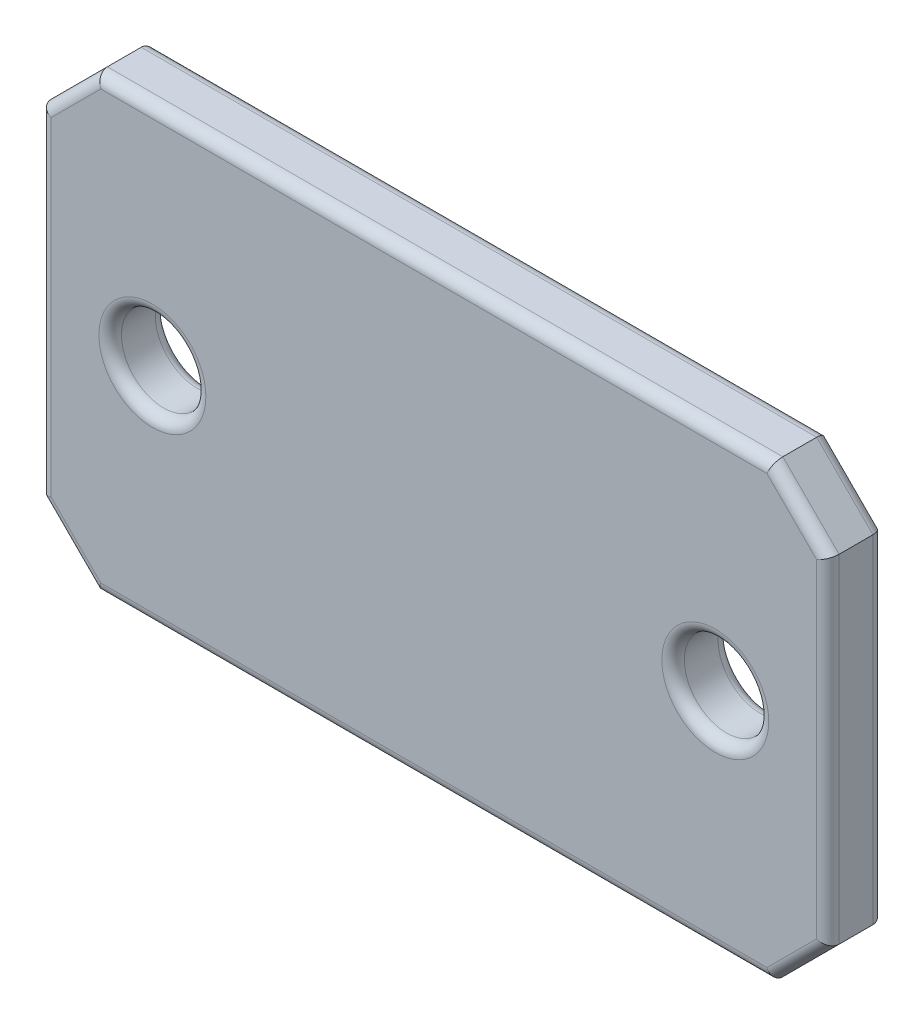
SolidWorks part; units mm, degrees
ref_plane "Front" through (0, 0, 0) normal (0, 0, 1) x (1, 0, 0)
ref_plane "Top" through (0, 0, 0) normal (0, 1, 0) x (1, 0, 0)
ref_plane "Right" through (0, 0, 0) normal (1, 0, 0) x (0, 0, -1)
sketch "Sketch1" plane through (0, 0, 0) normal (0, 0, 1) x (1, 0, 0)
  line L8 (19.05, 12.7) -> (-19.05, 12.7)
  line L9 (-19.05, 12.7) -> (-22.225, 9.525)
  line L10 (-22.225, 9.525) -> (-22.225, -9.525)
  line L11 (-22.225, -9.525) -> (-19.05, -12.7)
  line L12 (-19.05, -12.7) -> (19.05, -12.7)
  line L13 (19.05, -12.7) -> (22.225, -9.525)
  line L14 (22.225, -9.525) -> (22.225, 9.525)
  line L15 (22.225, 9.525) -> (19.05, 12.7)
  line L16 (19.05, 12.7) -> (-19.05, 12.7)
  line L17 (-19.05, 12.7) -> (-22.225, 9.525)
  line L18 (-22.225, 9.525) -> (-22.225, -9.525)
  line L19 (-22.225, -9.525) -> (-19.05, -12.7)
  line L20 (-19.05, -12.7) -> (19.05, -12.7)
  line L21 (19.05, -12.7) -> (22.225, -9.525)
  line L22 (22.225, -9.525) -> (22.225, 9.525)
  line L23 (22.225, 9.525) -> (19.05, 12.7)
  dimension "D1" = 0
extrude "Boss-Extrude1" add sketch "Sketch1" along normal blind 3.175
hole_wizard "3/16 (0.1875) Diameter Hole1" positions "Sketch2" profile "Sketch3" hole size "3/16" standard "ANSI Inch" end condition through all
sketch "Sketch2" plane through (0, 0, 3.175) normal (0, 0, 1) x (1, 0, 0)
  circle A0 centre (-15.875, 0) radius 2.5527 construction
  circle A1 centre (15.875, 0) radius 2.5527 construction
  point P2 (15.875, 0)
  point P4 (-15.875, 0)
  point P9 (0, 0)
sketch "Sketch3" plane through (15.875, 0, 3.175) normal (1, 0, 0) x (0, -1, 0)
  line L0 (0, 0) -> (0, 3.175)
  line L1 (0, 3.175) -> (2.3812, 3.175)
  line L2 (2.3812, 3.175) -> (2.3812, 0)
  line L5 (2.3812, 0) -> (0, 0)
  line L11 (0, -6.35) -> (0, 107.95) construction
  dimension "Thru Hole Dia." = 4.7625
  dimension "Thru Hole Depth" = 3.175
fillet "Fillet1" radius 0.635 20 edges at (22.225, 0, 3.175) (20.6375, -11.1125, 3.175) (0, -12.7, 3.175) (-20.6375, -11.1125, 3.175) (-22.225, 0, 3.175) (-20.6375, 11.1125, 3.175) (0, 12.7, 3.175) (20.6375, 11.1125, 3.175) (-13.4938, 0, 3.175) (18.2562, 0, 3.175) (0, 12.7, 0) (-20.6375, 11.1125, 0) (-22.225, 0, 0) (-20.6375, -11.1125, 0) (0, -12.7, 0) (20.6375, -11.1125, 0) (22.225, 0, 0) (20.6375, 11.1125, 0) (-13.4938, 0, 0) (18.2563, 0, 0)
